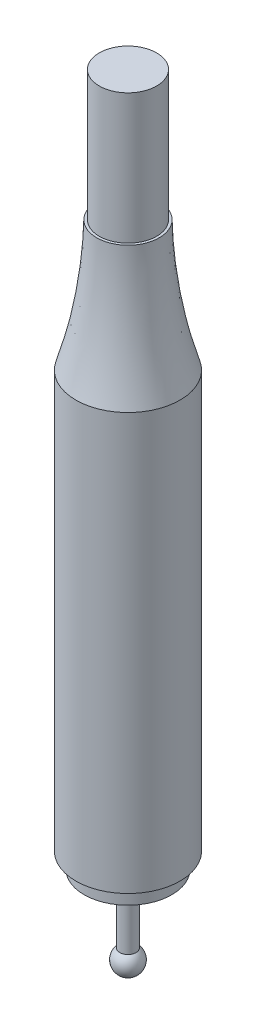
SolidWorks part; units mm, degrees
ref_plane "Front Plane" through (0, 0, 0) normal (0, 0, 1) x (1, 0, 0)
ref_plane "Top Plane" through (0, 0, 0) normal (0, 1, 0) x (1, 0, 0)
ref_plane "Right Plane" through (0, 0, 0) normal (1, 0, 0) x (0, 0, -1)
sketch "Sketch1" plane through (0, 0, 0) normal (0, 0, 1) x (1, 0, 0)
  line L0 (12.7, 0) -> (10.7, 0)
  line L1 (12.7, 0) -> (12.7, 101.6)
  line L2 (7, 133.35) -> (7.62, 133.35)
  line L3 (0, 165.1) -> (0, -34.0603) construction
  line L4 (0, 165.1) -> (0, -26.1094)
  line L5 (10.7, 0) -> (10.7, -3.8844)
  line L6 (0, 165.1) -> (7, 165.1)
  line L7 (7, 165.1) -> (7, 133.35)
  line L8 (10.7, -3.8844) -> (1.9844, -3.8844)
  line L9 (1.9844, -3.8844) -> (1.9844, -20.4559)
  arc A0 (0, -26.1094) -> (1.9844, -20.4559) centre (0, -22.9344) ccw
  spline S1 degree 2 poles (12.7, 101.6) (7.9659, 117.1199) (7.62, 133.35) knots 0 0 0 1 1 1
  dimension "D4" = 2
  dimension "D5" = 7
revolve "Revolve3" add sketch "Sketch1" angle 360 about L3
